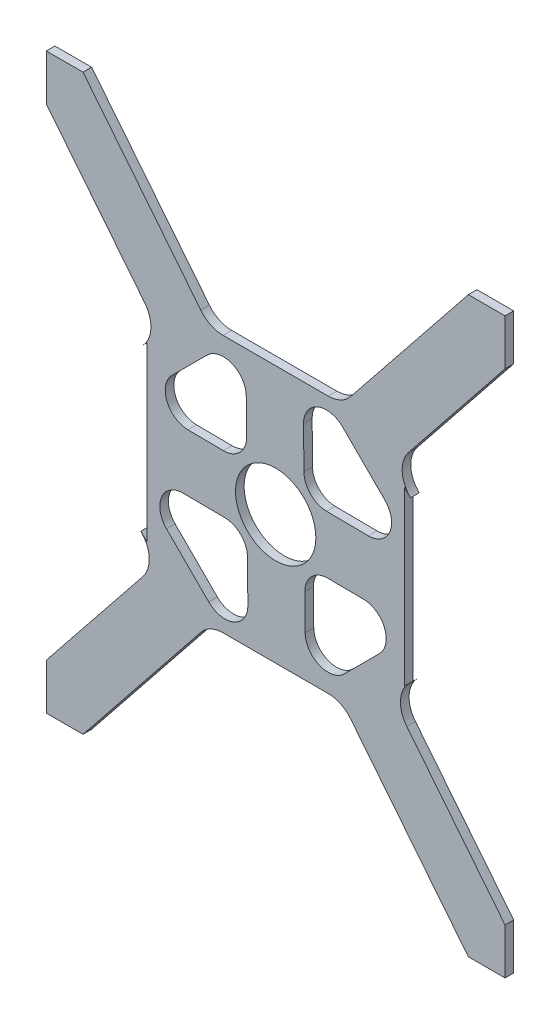
SolidWorks part; units mm, degrees
ref_plane "Front Plane" through (0, 0, 0) normal (0, 0, 1) x (1, 0, 0)
ref_plane "Top Plane" through (0, 0, 0) normal (0, 1, 0) x (1, 0, 0)
ref_plane "Right Plane" through (0, 0, 0) normal (1, 0, 0) x (0, 0, -1)
sketch "Sketch1" plane through (0, 0, 0) normal (0, 0, 1) x (1, 0, 0)
  line L0 (0.6673, 60.7823) -> (0.5424, 60.9072)
  line L1 (0.6673, 74.9245) -> (-74.9245, -0.6673)
  line L2 (0.6673, 74.9245) -> (74.9245, 0.6673)
  line L3 (74.9245, 0.6673) -> (-0.6673, -74.9245)
  line L4 (-74.9245, -0.6673) -> (-0.6673, -74.9245)
  line L5 (0.6673, 74.9245) -> (-0.6673, -74.9245) construction
  line L6 (74.9245, 0.6673) -> (-74.9245, -0.6673) construction
  line L7 (36.1871, -23.928) -> (23.928, -36.1871)
  line L8 (-60.7823, -0.6673) -> (-60.9072, -0.5424)
  line L9 (-23.928, 36.1871) -> (-36.1871, 23.928)
  line L10 (-38.0792, -23.3704) -> (-23.3704, -38.0792)
  line L11 (-0.5424, -60.9072) -> (-0.6673, -60.7823)
  line L14 (10.1619, -18.2324) -> (10.2714, -30.6011)
  line L16 (-17.7718, -9.843) -> (-32.3515, -9.7138)
  line L17 (-60.7823, -0.6673) -> (-0.6673, -60.7823) construction
  line L18 (-9.843, -17.7718) -> (-9.7138, -32.3515)
  line L20 (-18.2324, 10.1619) -> (-30.6011, 10.2714)
  line L21 (9.7138, 32.3515) -> (9.843, 17.7718)
  line L22 (30.6011, -10.2714) -> (18.2324, -10.1619)
  line L23 (60.7823, 0.6673) -> (-0.6673, -60.7823) construction
  line L24 (32.3515, 9.7138) -> (17.7718, 9.843)
  line L25 (60.9072, 0.5424) -> (60.7823, 0.6673)
  line L26 (0.6673, 60.7823) -> (60.7823, 0.6673) construction
  line L27 (0.6673, 60.7823) -> (-60.7823, -0.6673) construction
  line L28 (23.3704, 38.0792) -> (38.0792, 23.3704)
  line L29 (-10.2714, 30.6011) -> (-10.1619, 18.2324)
  arc A0 (-18.2324, 10.1619) -> (-10.1619, 18.2324) centre (-18.1616, 18.1616) ccw
  arc A1 (-30.6011, 10.2714) -> (-36.1871, 23.928) centre (-30.5302, 18.2711) cw
  arc A2 (-23.928, 36.1871) -> (-10.2714, 30.6011) centre (-18.2711, 30.5302) cw
  arc A3 (23.3704, 38.0792) -> (9.7138, 32.3515) centre (17.7135, 32.4223) ccw
  arc A4 (9.843, 17.7718) -> (17.7718, 9.843) centre (17.8427, 17.8427) ccw
  arc A5 (32.3515, 9.7138) -> (38.0792, 23.3704) centre (32.4223, 17.7135) ccw
  arc A6 (-9.843, -17.7718) -> (-17.7718, -9.843) centre (-17.8427, -17.8427) ccw
  arc A7 (-32.3515, -9.7138) -> (-38.0792, -23.3704) centre (-32.4223, -17.7135) ccw
  arc A8 (-23.3704, -38.0792) -> (-9.7138, -32.3515) centre (-17.7135, -32.4223) ccw
  arc A9 (18.2324, -10.1619) -> (10.1619, -18.2324) centre (18.1616, -18.1616) ccw
  arc A10 (10.2714, -30.6011) -> (23.928, -36.1871) centre (18.2711, -30.5302) ccw
  arc A11 (30.6011, -10.2714) -> (36.1871, -23.928) centre (30.5302, -18.2711) cw
  circle A12 centre (0, 0) radius 14
  point P0 (0, 0)
  dimension "D2" = 8
  dimension "D1" = 10
extrude "Boss-Extrude1" add sketch "Sketch1" along normal blind 3
sketch "Sketch2" plane through (0, 0, 3) normal (0, 0, 1) x (1, 0, 0)
  line L1 (44.9245, -44.9245) -> (-44.9245, -44.9245)
  line L2 (44.9245, -44.9245) -> (44.9245, 44.9245)
  line L3 (44.9245, 44.9245) -> (-44.9245, 44.9245)
  line L4 (-44.9245, -44.9245) -> (-44.9245, 44.9245)
  line L5 (44.9245, -44.9245) -> (-44.9245, 44.9245) construction
  line L6 (44.9245, 44.9245) -> (-44.9245, -44.9245) construction
  point P0 (0, 0)
  dimension "D1" = 30
  dimension "D2" = 30
extrude "Cut-Extrude1" cut sketch "Sketch2" against normal blind 3 flip side to cut
sketch "Sketch3" plane through (0, 0, 3) normal (0, 0, 1) x (1, 0, 0)
  line L0 (-67.1938, -100) -> (-26.1358, -48.6775)
  line L1 (-80, -100) -> (-67.1938, -100)
  line L2 (-80, -100) -> (-80, -83.9922)
  line L3 (-80, 100) -> (-67.1938, 100)
  line L4 (80, -100) -> (80, -83.9922)
  line L5 (-80, -100) -> (80, 100) construction
  line L6 (-80, 100) -> (80, -100) construction
  line L7 (-80, -83.9922) -> (-46.3022, -41.8699)
  line L8 (-80, 83.9922) -> (-45.7091, 41.1285)
  line L9 (-67.1938, 100) -> (-26.1358, 48.6775)
  line L10 (67.1938, -100) -> (80, -100)
  line L46 (26.1358, 48.6775) -> (67.1938, 100)
  line L47 (-87.8087, -93.753) -> (72.1913, 106.247) construction
  line L48 (46.3022, 41.8699) -> (80, 83.9922)
  line L49 (-72.1913, -106.247) -> (87.8087, 93.753) construction
  line L50 (45.7091, -41.1285) -> (80, -83.9922)
  line L51 (-72.1913, 106.247) -> (87.8087, -93.753) construction
  line L52 (26.1358, -48.6775) -> (67.1938, -100)
  line L53 (-87.8087, 93.753) -> (72.1913, -106.247) construction
  line L54 (44.9245, 30.6673) -> (30.6673, 44.9245)
  line L55 (44.9245, -29.3327) -> (44.9245, 30.6673)
  line L56 (29.3327, -44.9245) -> (44.9245, -29.3327)
  line L57 (-30.6673, -44.9245) -> (29.3327, -44.9245)
  line L58 (-44.9245, -30.6673) -> (-30.6673, -44.9245)
  line L59 (-44.9245, 29.3327) -> (-44.9245, -30.6673)
  line L60 (-29.3327, 44.9245) -> (-44.9245, 29.3327)
  line L61 (30.6673, 44.9245) -> (-29.3327, 44.9245)
  line L62 (44.9245, 30.6673) -> (47.0398, 28.5519)
  line L63 (44.9245, -29.3327) -> (44.9245, 30.6673)
  line L64 (46.4467, -27.8105) -> (44.9245, -29.3327)
  line L65 (-18.3271, -44.9245) -> (18.3271, -44.9245)
  line L66 (-44.9245, -30.6673) -> (-47.0398, -28.5519)
  line L67 (-44.9245, 29.3327) -> (-44.9245, -30.6673)
  line L68 (-46.4467, 27.8105) -> (-44.9245, 29.3327)
  line L69 (18.3271, 44.9245) -> (-18.3271, 44.9245)
  line L70 (67.1938, 100) -> (80, 100)
  line L71 (-80, 83.9922) -> (-80, 100)
  line L72 (80, 83.9922) -> (80, 100)
  arc A0 (18.3271, -44.9245) -> (26.1358, -48.6775) centre (18.3271, -54.9245) cw
  arc A1 (-18.3271, -44.9245) -> (-26.1358, -48.6775) centre (-18.3271, -54.9245) ccw
  arc A2 (-46.3022, -41.8699) -> (-47.0398, -28.5519) centre (-54.1109, -35.623) ccw
  arc A3 (-46.4467, 27.8105) -> (-45.7091, 41.1285) centre (-53.5178, 34.8816) ccw
  arc A4 (-18.3271, 44.9245) -> (-26.1358, 48.6775) centre (-18.3271, 54.9245) cw
  arc A5 (18.3271, 44.9245) -> (26.1358, 48.6775) centre (18.3271, 54.9245) ccw
  arc A6 (47.0398, 28.5519) -> (46.3022, 41.8699) centre (54.1109, 35.623) cw
  arc A7 (45.7091, -41.1285) -> (46.4467, -27.8105) centre (53.5178, -34.8816) cw
  point P0 (0, 0)
  line M26 (-29.3327, 44.9245) -> (-44.9245, 29.3327)
  line M28 (-44.9245, -30.6673) -> (-30.6673, -44.9245)
  line M29 (-30.6673, -44.9245) -> (29.3327, -44.9245)
  line M30 (29.3327, -44.9245) -> (44.9245, -29.3327)
  line M32 (44.9245, 30.6673) -> (30.6673, 44.9245)
  line M33 (30.6673, 44.9245) -> (-29.3327, 44.9245)
  dimension "D6" = 10
  dimension "D7" = 160
  dimension "D8" = 200
  dimension "D1" = 10
  dimension "D2" = 10
  dimension "D3" = 10
  dimension "D4" = 10
  dimension "D5" = 0
extrude "Boss-Extrude2" add sketch "Sketch3" against normal blind 3 contours L48 L72 L70 L46 M33 M32 | L71 L8 L9 L3 M26 M33 | L7 L2 L1 L0 M29 M28 | L52 L10 L4 L50 M29 M30
